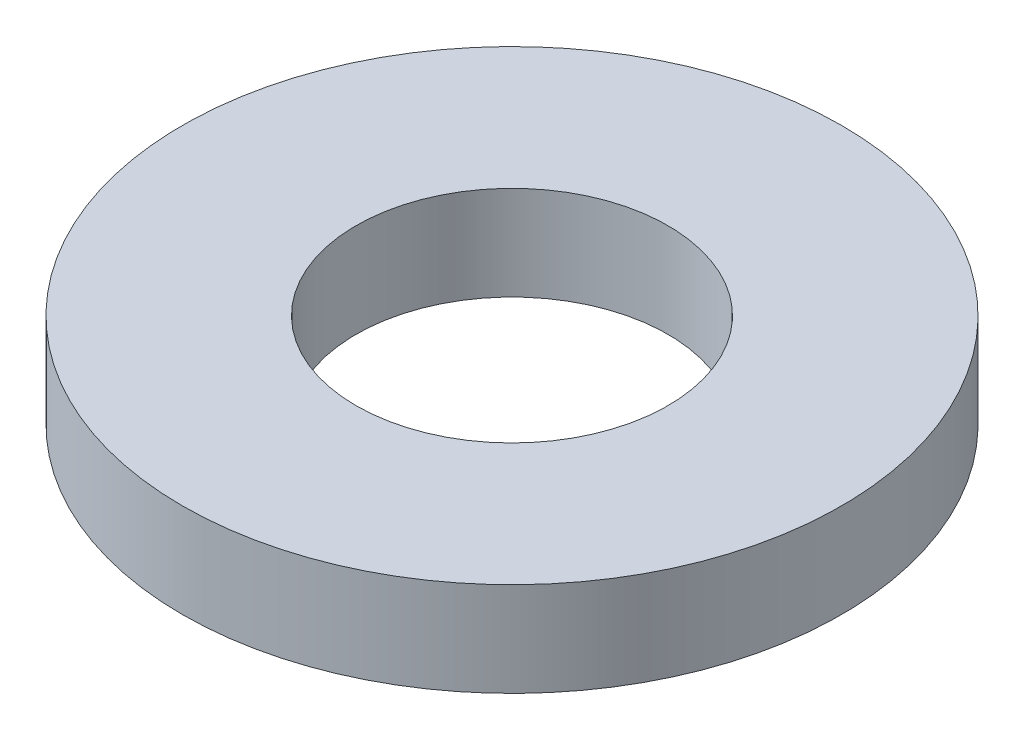
SolidWorks part; units mm, degrees
material "Nylon 101"
ref_plane "Front Plane" through (0, 0, 0) normal (0, 0, 1) x (1, 0, 0)
ref_plane "Top Plane" through (0, 0, 0) normal (0, 1, 0) x (1, 0, 0)
ref_plane "Right Plane" through (0, 0, 0) normal (1, 0, 0) x (0, 0, -1)
sketch "Sketch1" plane through (0, 0, 0) normal (1, 0, 0) x (0, 0, -1)
  line L0 (0, 39.6767) -> (0, -35.3784) construction
  line L6 (1.325, 1.1269) -> (2.8, 1.1269)
  line L7 (1.325, 1.1269) -> (1.325, 0.3269)
  line L8 (1.325, 0.3269) -> (2.8, 0.3269)
  line L9 (2.8, 1.1269) -> (2.8, 0.3269)
  dimension "D2" = 0.8
  dimension "D3" = 5.6
  dimension "D4" = 2.65
revolve "Revolve2" add sketch "Sketch1" angle 360 about L0
